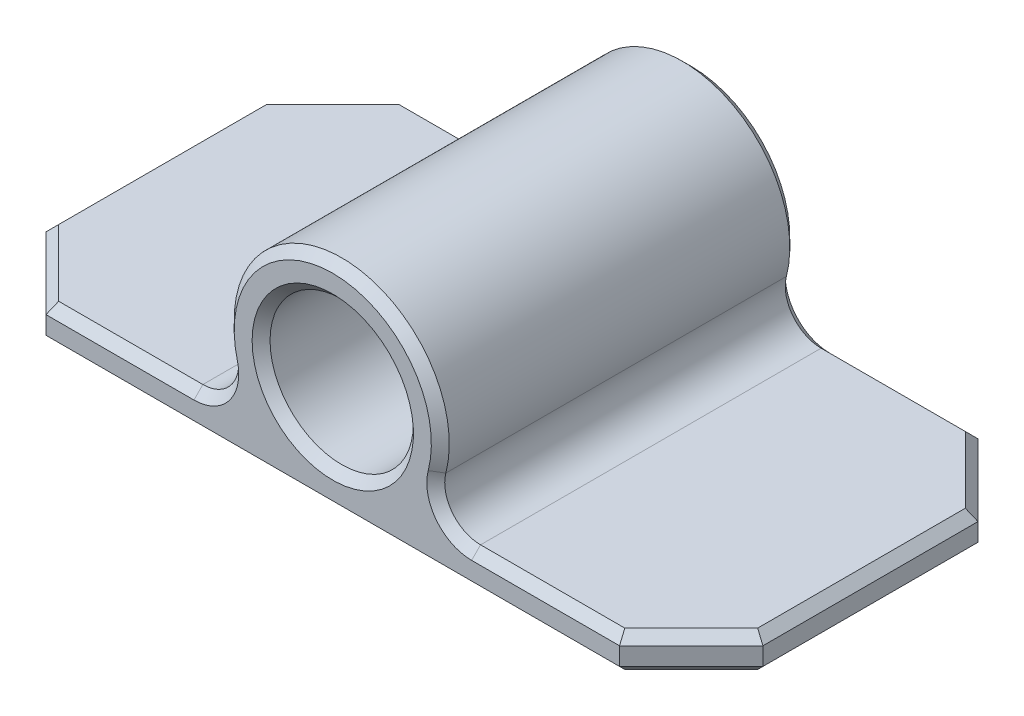
SolidWorks part; units mm, degrees
ref_plane "Plan de face" through (0, 0, 0) normal (0, 0, 1) x (1, 0, 0)
ref_plane "Plan de dessus" through (0, 0, 0) normal (0, 1, 0) x (1, 0, 0)
ref_plane "Plan de droite" through (0, 0, 0) normal (1, 0, 0) x (0, 0, -1)
sketch "Esquisse1" plane through (0, 0, 0) normal (0, 0, 1) x (1, 0, 0)
  line L0 (-10, -3) -> (10, -3)
  line L1 (-10, -2) -> (-3.873, -2)
  line L2 (3.873, -2) -> (10, -2)
  line L3 (-10, -2) -> (-10, -3)
  line L4 (10, -2) -> (10, -3)
  line L5 (0, 0) -> (0, -3) construction
  circle A0 centre (0, 0) radius 1
  arc A1 (2.9047, -0.75) -> (-2.9047, -0.75) centre (0, 0) ccw
  arc A2 (-2.9047, -0.75) -> (-3.873, -2) centre (-3.873, -1) cw
  arc A3 (3.873, -2) -> (2.9047, -0.75) centre (3.873, -1) cw
  dimension "D1" = 2
  dimension "D2" = 6
  dimension "D5" = 1
  dimension "D6" = 1
  dimension "D3" = 20
  dimension "D4" = 1
extrude "Boss.-Extru.1" add sketch "Esquisse1" along normal blind 10
sketch "Esquisse2" plane through (0, 0, 10) normal (0, 0, 1) x (1, 0, 0)
  circle A0 centre (0, 0) radius 2
  dimension "D1" = 4
extrude "Enlèv. mat.-Extru.1" cut sketch "Esquisse2" against normal blind 8
chamfer "Chanfrein1" distance 2 angle 45 4 edges at (-10, -2.5, 10) (-10, -2.5, 0) (10, -2.5, 0) (10, -2.5, 10)
chamfer "Chanfrein2" distance 0.25 angle 45 26 edges at (-9, -2, 9) (-10, -2, 5) (-9, -2, 1) (2, 0, 10) (1, 0, 0) (-5.9365, -2, 10) (-5.9365, -2, 0) (-3.0824, -1.6124, 10) (-3.0824, -1.6124, 0) (0, 3, 10) (0, 3, 0) (3.0824, -1.6124, 10) (3.0824, -1.6124, 0) (5.9365, -2, 10) (9, -2, 9) (10, -2, 5) (9, -2, 1) (5.9365, -2, 0) (-9, -3, 9) (-10, -3, 5) (-9, -3, 1) (0, -3, 10) (9, -3, 9) (10, -3, 5) (9, -3, 1) (0, -3, 0)
